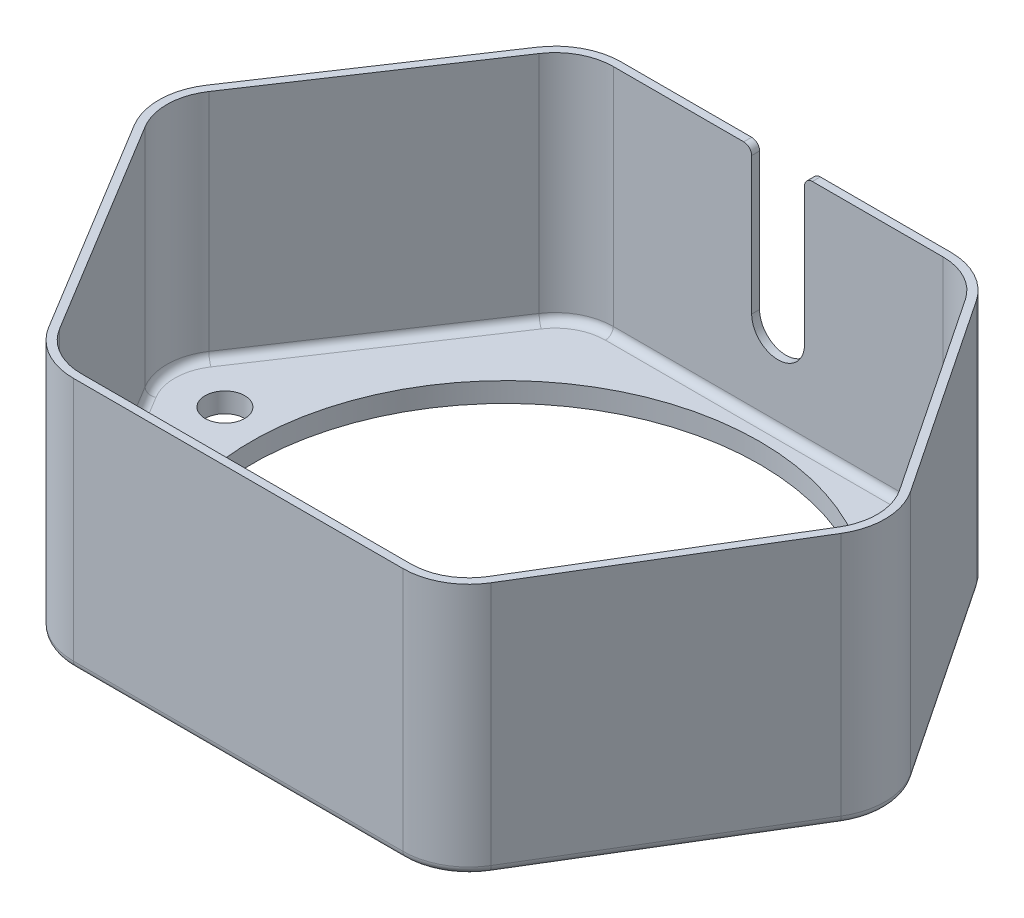
SolidWorks part; units mm, degrees
material "ABS"
ref_plane "Plan de face" through (0, 0, 0) normal (0, 0, 1) x (1, 0, 0)
ref_plane "Plan de dessus" through (0, 0, 0) normal (0, 1, 0) x (1, 0, 0)
ref_plane "Plan de droite" through (0, 0, 0) normal (1, 0, 0) x (0, 0, -1)
sketch "Esquisse1" plane through (0, 0, 0) normal (0, 1, 0) x (1, 0, 0)
  line L0 (0, 40) -> (0, 36)
  line L1 (0, -43) -> (-24.9647, -43)
  line L2 (-33.5126, -38.1897) -> (-53.5479, -5.1897)
  line L3 (-53.316, 5.5538) -> (-33.2807, 35.5538)
  line L4 (-24.9647, 40) -> (0, 40)
  line L5 (0, -41) -> (0, -43)
  arc A0 (-24.9647, -43) -> (-33.5126, -38.1897) centre (-24.9647, -33) cw
  arc A1 (-53.5479, -5.1897) -> (-53.316, 5.5538) centre (-45, 0) cw
  arc A2 (-33.2807, 35.5538) -> (-24.9647, 40) centre (-24.9647, 30) cw
  circle A3 centre (-45, 0) radius 3
  arc A4 (0, 36) -> (0, -41) centre (0, -2.5) ccw
  point P13 (-45, 0)
  dimension "D1" = 10
  dimension "D6" = 6
  dimension "D7" = 40
  dimension "D9" = 2.5
  dimension "D10" = 38.5
  dimension "D2" = 115
  dimension "D3" = 83
  dimension "D4" = 45
  dimension "D5" = 10
  dimension "D8" = 43
extrude "Boss.-Extru.1" add sketch "Esquisse1" along normal blind 3
sketch "Esquisse2" plane through (0, 3, 0) normal (0, 1, 0) x (1, 0, 0)
  line L0 (0, 40) -> (-24.9647, 40) construction
  line L1 (-33.2807, 35.5538) -> (-53.316, 5.5538) construction
  line L2 (-53.5479, -5.1897) -> (-33.5126, -38.1897) construction
  line L3 (-24.9647, -43) -> (0, -43) construction
  line L4 (0, 40) -> (-24.9647, 40)
  line L5 (-33.2807, 35.5538) -> (-53.316, 5.5538)
  line L6 (-53.5479, -5.1897) -> (-33.5126, -38.1897)
  line L7 (-24.9647, -43) -> (0, -43)
  arc A0 (-24.9647, 40) -> (-33.2807, 35.5538) centre (-24.9647, 30) ccw construction
  arc A1 (-53.316, 5.5538) -> (-53.5479, -5.1897) centre (-45, 0) ccw construction
  arc A2 (-33.5126, -38.1897) -> (-24.9647, -43) centre (-24.9647, -33) ccw construction
  arc A3 (-24.9647, 40) -> (-33.2807, 35.5538) centre (-24.9647, 30) ccw
  arc A4 (-53.316, 5.5538) -> (-53.5479, -5.1897) centre (-45, 0) ccw
  arc A5 (-33.5126, -38.1897) -> (-24.9647, -43) centre (-24.9647, -33) ccw
extrude "Extru.-Mince1" add sketch "Esquisse2" along normal blind 35.3 thin thin type one direction reverse wall 1.2
sketch "Esquisse3" plane through (0, 0, -40) normal (0, 0, -1) x (-1, 0, 0)
  line L0 (0, 16.3) -> (0, 38.3) construction
  line L1 (0, 38.3) -> (0, 0) construction
  line L2 (-4, 16.3) -> (-4, 38.3)
  line L3 (4, 16.3) -> (4, 38.3)
  line L4 (0, 38.3) -> (24.9647, 38.3) construction
  arc A0 (-4, 16.3) -> (4, 16.3) centre (0, 16.3) ccw
  arc A1 (4, 38.3) -> (-4, 38.3) centre (0, 38.3) ccw
  point P5 (0, 27.3)
  dimension "D2" = 22
  dimension "D1" = 8
extrude "Enlèv. mat.-Extru.1" cut sketch "Esquisse3" against normal blind 10
fillet "Congé1" radius 1.2 15 edges at (-29.2804, 3, 40.6691) (-42.5045, 3, 21.0669) (-53.7979, 3, -0.1899) (-42.3004, 3, -19.8873) (-29.1139, 3, -37.7604) (-4, 38.3, -39.4) (-12.4823, 0, -40) (-29.6797, 0, -38.8187) (-43.2983, 0, -20.5538) (-54.9977, 0, -0.2158) (-43.5303, 0, 21.6897) (-29.8689, 0, 41.7148) (-12.4823, 0, 43)
mirror "Symétrie1" about plane through (0, 3, 41) normal (-1, 0, 0) of bodies 103
